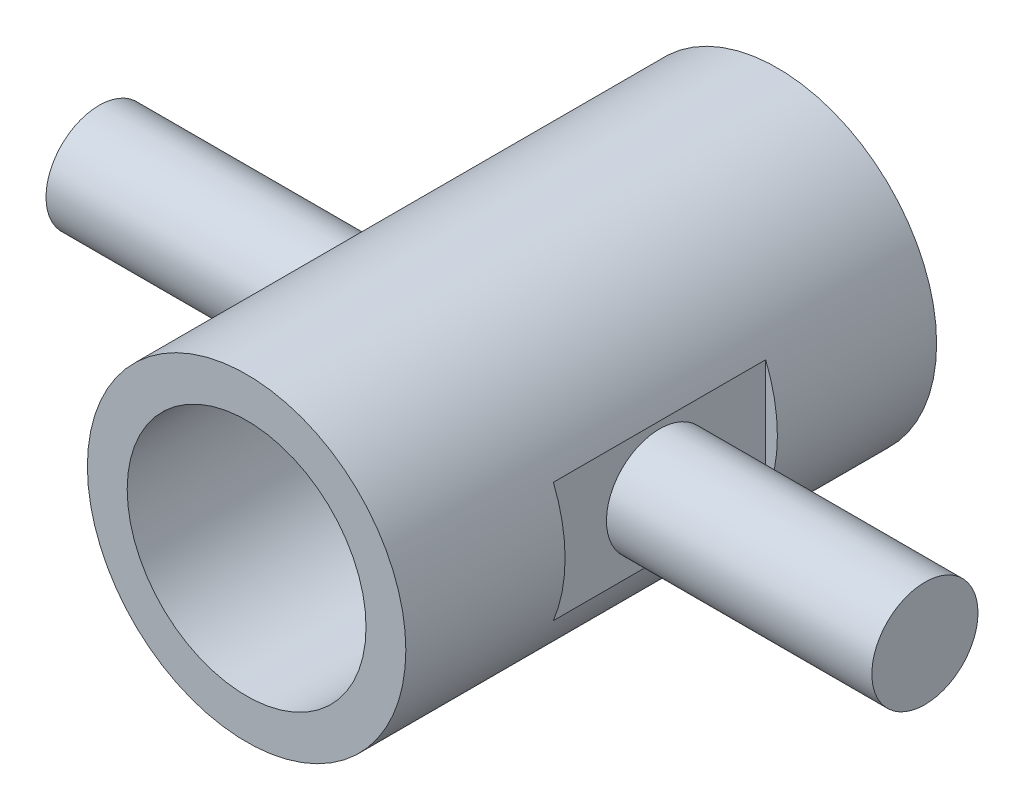
SolidWorks part; units mm, degrees
ref_plane "Front Plane" through (0, 0, 0) normal (0, 0, 1) x (1, 0, 0)
ref_plane "Top Plane" through (0, 0, 0) normal (0, 1, 0) x (1, 0, 0)
ref_plane "Right Plane" through (0, 0, 0) normal (1, 0, 0) x (0, 0, -1)
sketch "Sketch1" plane through (0, 0, 0) normal (0, 0, 1) x (1, 0, 0)
  circle A0 centre (0, 0) radius 2.25
  circle A1 centre (0, 0) radius 3
  dimension "D1" = 4.5
  dimension "D2" = 6
extrude "Boss-Extrude1" add sketch "Sketch1" along normal blind 10
sketch "Sketch2" plane through (0, 0, 10) normal (0, 0, 1) x (1, 0, 0)
  line L0 (-3.164, 0) -> (3.1801, 0) construction
  line L1 (0, 2.1268) -> (0, -2.1349) construction
  line L2 (-3.9005, 1.1287) -> (-2.7796, 1.1287)
  line L3 (-3.9005, 1.1287) -> (-3.9005, -1.1287)
  line L4 (-3.9005, -1.1287) -> (-2.7796, -1.1287)
  line L5 (-2.7796, 1.1287) -> (-2.7796, -1.1287)
  line L6 (-3.9005, 1.1287) -> (-2.7796, -1.1287) construction
  line L7 (-3.9005, -1.1287) -> (-2.7796, 1.1287) construction
  line L8 (3.9005, -1.1287) -> (2.7796, -1.1287)
  line L9 (2.7796, 1.1287) -> (2.7796, -1.1287)
  line L10 (3.9005, 1.1287) -> (3.9005, -1.1287)
  line L11 (3.9005, 1.1287) -> (2.7796, 1.1287)
  circle A0 centre (0, 0) radius 3 construction
  point P3 (-3.34, 0)
extrude "Cut-Extrude3" cut sketch "Sketch2" against normal blind 4 from offset 3 offset against normal yes
sketch "Sketch3" plane through (-2.7796, 0, 0) normal (-1, 0, 0) x (0, 0, 1)
  line L0 (7, -1.1287) -> (7, 1.1287) construction
  circle A0 centre (5, 0) radius 1
  dimension "D1" = 2
  dimension "D2" = 2
extrude "Boss-Extrude2" add sketch "Sketch3" along normal blind 5
sketch "Sketch4" plane through (2.7796, 0, 0) normal (1, 0, 0) x (0, 0, -1)
  circle A1 centre (-5, 0) radius 1
  circle A2 centre (-5, 0) radius 1
  dimension "D1" = 0
extrude "Boss-Extrude3" add sketch "Sketch4" along normal blind 5
